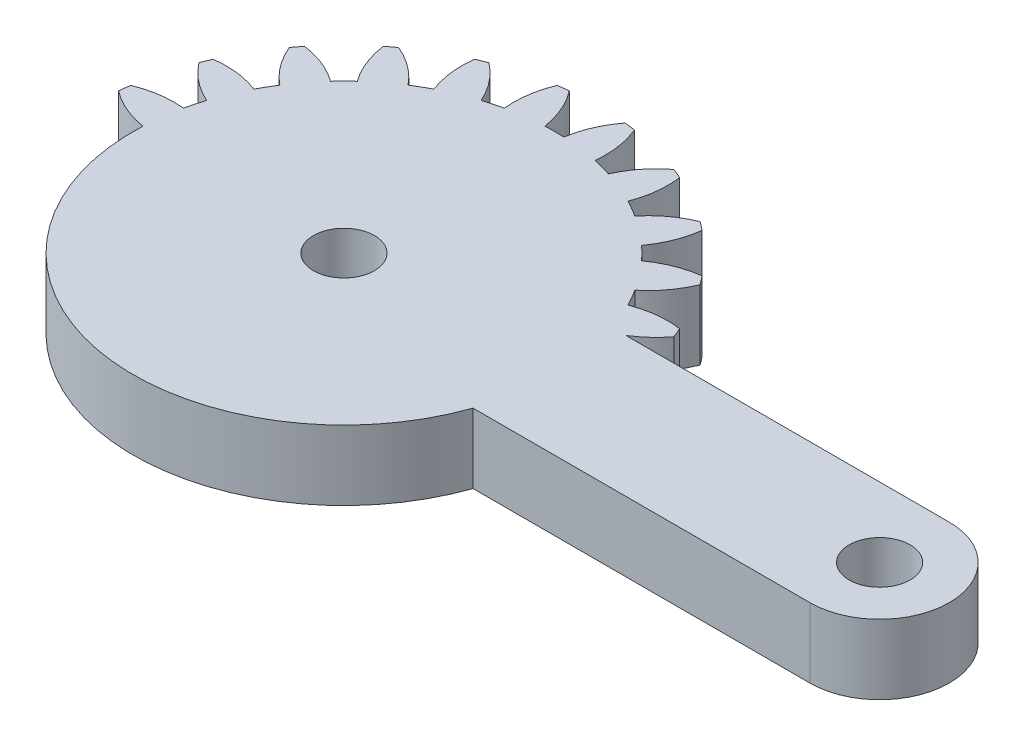
SolidWorks part; units mm, degrees
ref_plane "Front Plane" through (0, 0, 0) normal (0, 0, 1) x (1, 0, 0)
ref_plane "Top Plane" through (0, 0, 0) normal (0, 1, 0) x (1, 0, 0)
ref_plane "Right Plane" through (0, 0, 0) normal (1, 0, 0) x (0, 0, -1)
ref_plane "Plane1" through (0, 4, 0) normal (0, 1, 0) x (1, 0, 0)
sketch "Sketch1" plane through (0, 4, 0) normal (0, 1, 0) x (1, 0, 0)
  line L0 (1.3057, -4) -> (20.6437, -4)
  line L1 (20.6437, 4) -> (2.0816, 4)
  arc A0 (-24.5622, 2.2179) -> (-24.6437, 1.5991) centre (-10.1063, 0) ccw
  arc A1 (-24.6437, 1.5991) -> (-22.1869, 0.5427) centre (-21.3486, 5.8773) ccw
  arc A2 (-22.1869, 0.5427) -> (1.3057, -4) centre (-10.1063, 0) ccw
  arc A3 (20.6437, -4) -> (20.6437, 4) centre (20.6437, 0) ccw
  arc A4 (2.0816, 4) -> (3.5217, 5.3071) centre (-0.7683, 8.5867) ccw
  arc A5 (3.5217, 5.3071) -> (3.2829, 5.8838) centre (-10.1063, 0) ccw
  arc A6 (3.2829, 5.8838) -> (0.6271, 5.5703) centre (2.5684, 0.5313) ccw
  arc A7 (0.6271, 5.5703) -> (0.0844, 6.5103) centre (-10.1063, 0) ccw
  arc A8 (0.0844, 6.5103) -> (1.6838, 8.6535) centre (-3.3089, 10.711) ccw
  arc A9 (1.6838, 8.6535) -> (1.3038, 9.1487) centre (-10.1063, 0) ccw
  arc A10 (1.3038, 9.1487) -> (-1.1803, 8.1585) centre (1.999, 3.7936) ccw
  arc A11 (-1.1803, 8.1585) -> (-1.9479, 8.926) centre (-10.1063, 0) ccw
  arc A12 (-1.9479, 8.926) -> (-0.9576, 11.4102) centre (-6.3127, 12.1053) ccw
  arc A13 (-0.9576, 11.4102) -> (-1.4528, 11.7901) centre (-10.1063, 0) ccw
  arc A14 (-1.4528, 11.7901) -> (-3.596, 10.1907) centre (0.6046, 6.7975) ccw
  arc A15 (-3.596, 10.1907) -> (-4.5361, 10.7334) centre (-10.1063, 0) ccw
  arc A16 (-4.5361, 10.7334) -> (-4.2225, 13.3892) centre (-9.5751, 12.6747) ccw
  arc A17 (-4.2225, 13.3892) -> (-4.7992, 13.6281) centre (-10.1063, 0) ccw
  arc A18 (-4.7992, 13.6281) -> (-6.4554, 11.5285) centre (-1.5196, 9.3381) ccw
  arc A19 (-6.4554, 11.5285) -> (-7.5039, 11.8094) centre (-10.1063, 0) ccw
  arc A20 (-7.5039, 11.8094) -> (-7.8884, 14.4558) centre (-12.8736, 12.3803) ccw
  arc A21 (-7.8884, 14.4558) -> (-8.5072, 14.5373) centre (-10.1063, 0) ccw
  arc A22 (-8.5072, 14.5373) -> (-9.5636, 12.0806) centre (-4.2291, 11.2423) ccw
  arc A23 (-9.5636, 12.0806) -> (-10.6491, 12.0806) centre (-10.1063, 0) ccw
  arc A24 (-10.6491, 12.0806) -> (-11.7054, 14.5373) centre (-15.9836, 11.2423) ccw
  arc A25 (-11.7054, 14.5373) -> (-12.3243, 14.4558) centre (-10.1063, 0) ccw
  arc A26 (-12.3243, 14.4558) -> (-12.7088, 11.8094) centre (-7.3391, 12.3803) ccw
  arc A27 (-12.7088, 11.8094) -> (-13.7573, 11.5285) centre (-10.1063, 0) ccw
  arc A28 (-13.7573, 11.5285) -> (-15.4135, 13.6281) centre (-18.6931, 9.3381) ccw
  arc A29 (-15.4135, 13.6281) -> (-15.9901, 13.3892) centre (-10.1063, 0) ccw
  arc A30 (-15.9901, 13.3892) -> (-15.6766, 10.7334) centre (-10.6376, 12.6747) ccw
  arc A31 (-15.6766, 10.7334) -> (-16.6166, 10.1907) centre (-10.1063, 0) ccw
  arc A32 (-16.6166, 10.1907) -> (-18.7599, 11.7901) centre (-20.8173, 6.7975) ccw
  arc A33 (-18.7599, 11.7901) -> (-19.255, 11.4102) centre (-10.1063, 0) ccw
  arc A34 (-19.255, 11.4102) -> (-18.2648, 8.926) centre (-13.9, 12.1053) ccw
  arc A35 (-18.2648, 8.926) -> (-19.0324, 8.1585) centre (-10.1063, 0) ccw
  arc A36 (-19.0324, 8.1585) -> (-21.5165, 9.1487) centre (-22.2117, 3.7936) ccw
  arc A37 (-21.5165, 9.1487) -> (-21.8965, 8.6535) centre (-10.1063, 0) ccw
  arc A38 (-21.8965, 8.6535) -> (-20.2971, 6.5103) centre (-16.9038, 10.711) ccw
  arc A39 (-20.2971, 6.5103) -> (-20.8398, 5.5703) centre (-10.1063, 0) ccw
  arc A40 (-20.8398, 5.5703) -> (-23.4956, 5.8838) centre (-22.7811, 0.5313) ccw
  arc A41 (-23.4956, 5.8838) -> (-23.7344, 5.3071) centre (-10.1063, 0) ccw
  arc A42 (-23.7344, 5.3071) -> (-21.6348, 3.6509) centre (-19.4444, 8.5867) ccw
  arc A43 (-21.6348, 3.6509) -> (-21.9157, 2.6025) centre (-10.1063, 0) ccw
  arc A44 (-21.9157, 2.6025) -> (-24.5622, 2.2179) centre (-22.4867, -2.7673) ccw
  circle A45 centre (20.6437, 0) radius 1.75
  circle A46 centre (-10.1063, 0) radius 1.75
extrude "Boss-Extrude1" add sketch "Sketch1" against normal blind 4
